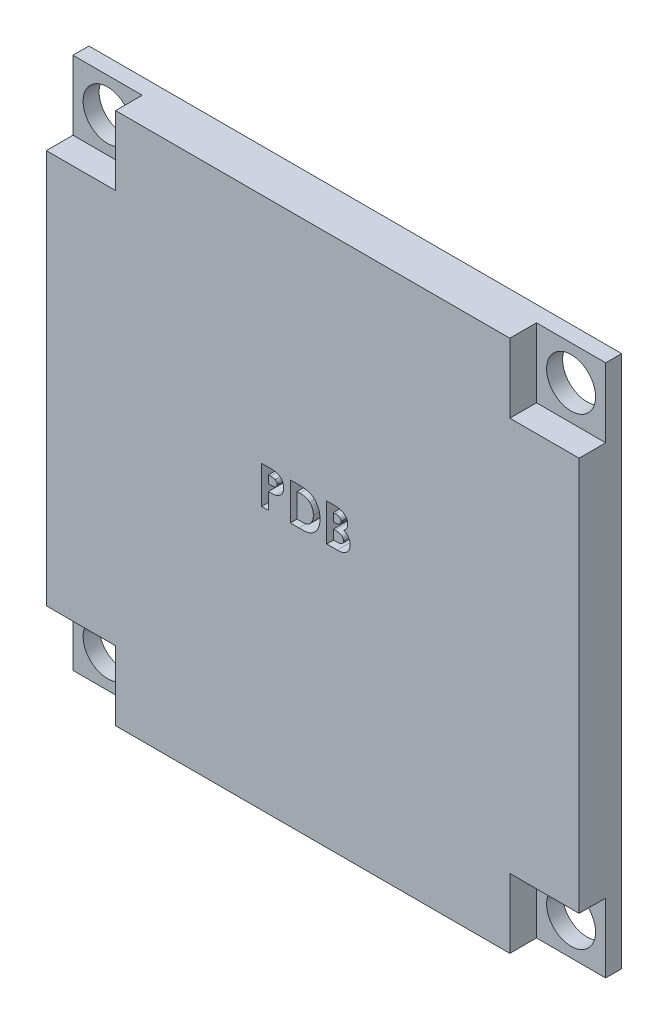
SolidWorks part; units mm, degrees
ref_plane "Front Plane" through (0, 0, 0) normal (0, 0, 1) x (1, 0, 0)
ref_plane "Top Plane" through (0, 0, 0) normal (0, 1, 0) x (1, 0, 0)
ref_plane "Right Plane" through (0, 0, 0) normal (1, 0, 0) x (0, 0, -1)
sketch "Sketch1" plane through (0, 0, 0) normal (0, 0, 1) x (1, 0, 0)
  line L1 (25, -25) -> (-25, -25)
  line L2 (25, -25) -> (25, 25)
  line L3 (25, 25) -> (-25, 25)
  line L4 (-25, -25) -> (-25, 25)
  line L5 (25, -25) -> (-25, 25) construction
  line L6 (25, 25) -> (-25, -25) construction
  point P0 (0, 0)
extrude "Boss-Extrude1" add sketch "Sketch1" along normal blind 4
sketch "Sketch2" plane through (0, 0, 4) normal (0, 0, 1) x (1, 0, 0)
  line L0 (25, 25) -> (18.5, 25)
  line L1 (25, 25) -> (25, 18.5)
  line L2 (18.5, 25) -> (18.5, 18.5)
  line L3 (25, 18.5) -> (18.5, 18.5)
  line L4 (25, 25) -> (-25, 25) construction
  line L5 (18.5, -25) -> (18.5, -18.5)
  line L6 (25, -18.5) -> (18.5, -18.5)
  line L7 (25, -25) -> (25, -18.5)
  line L8 (25, -25) -> (18.5, -25)
  line L9 (-25, -18.5) -> (-18.5, -18.5)
  line L10 (-18.5, -25) -> (-18.5, -18.5)
  line L11 (-25, -25) -> (-18.5, -25)
  line L12 (-25, -25) -> (-25, -18.5)
  line L13 (-18.5, 25) -> (-18.5, 18.5)
  line L14 (-25, 18.5) -> (-18.5, 18.5)
  line L15 (-25, 25) -> (-25, 18.5)
  line L16 (-25, 25) -> (-18.5, 25)
  point P22 (0, 0)
  dimension "D1" = 4
extrude "Cut-Extrude1" cut sketch "Sketch2" against normal blind 2.5
sketch "Sketch3" plane through (0, 0, 1.5) normal (0, 0, 1) x (1, 0, 0)
  circle A0 centre (-21.75, 21.75) radius 2.2981
  circle A1 centre (21.75, 21.75) radius 2.2981
  circle A2 centre (21.75, -21.75) radius 2.2981
  circle A3 centre (-21.75, -21.75) radius 2.2981
  point P23 (0, 0)
  dimension "D1" = 4
extrude "Cut-Extrude2" cut sketch "Sketch3" against normal blind 2.5
sketch "Sketch4" plane through (0, 0, 4) normal (0, 0, 1) x (1, 0, 0)
  text T0 "<b>PDB</b>"
extrude "Cut-Extrude3" cut sketch "Sketch4" against normal blind 2
